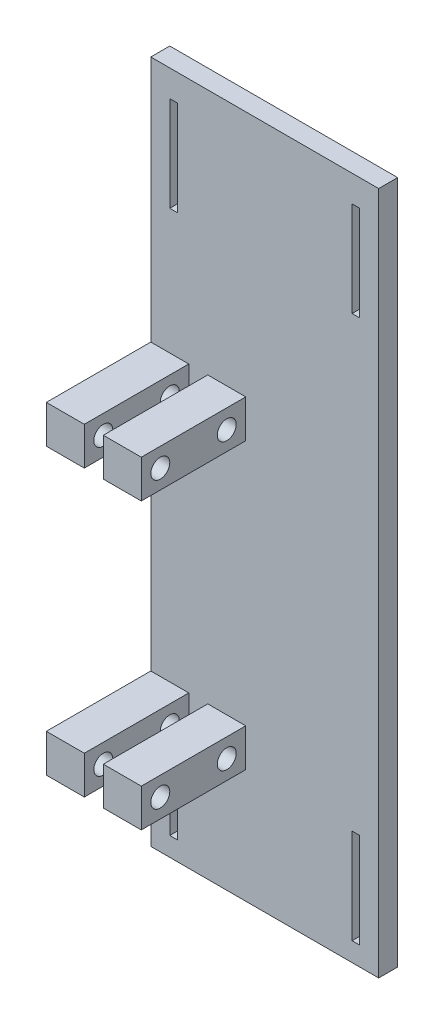
SolidWorks part; units mm, degrees
ref_plane "Alzado" through (0, 0, 0) normal (0, 0, 1) x (1, 0, 0)
ref_plane "Planta" through (0, 0, 0) normal (0, 1, 0) x (1, 0, 0)
ref_plane "Vista lateral" through (0, 0, 0) normal (1, 0, 0) x (0, 0, -1)
sketch "Croquis1" plane through (0, 0, 0) normal (0, 0, 1) x (1, 0, 0)
  line L1 (0, 0) -> (60, 0)
  line L2 (0, 0) -> (0, 170)
  line L3 (0, 170) -> (60, 170)
  line L4 (60, 0) -> (60, 170)
  dimension "D1" = 170
  dimension "D2" = 60
extrude "Saliente-Extruir1" add sketch "Croquis1" along normal blind 5
sketch "Croquis2" plane through (0, 0, 5) normal (0, 0, 1) x (1, 0, 0)
  line L0 (0, 170) -> (0, 0) construction
  line L1 (0, 105) -> (10, 105)
  line L2 (0, 105) -> (0, 95)
  line L3 (0, 95) -> (10, 95)
  line L4 (10, 105) -> (10, 95)
  line L5 (60, 170) -> (0, 170) construction
  line L6 (0, 30) -> (10, 30)
  line L7 (0, 30) -> (0, 20)
  line L8 (0, 20) -> (10, 20)
  line L9 (10, 30) -> (10, 20)
  line L11 (10, 105) -> (15, 105)
  line L12 (10, 105) -> (10, 95)
  line L13 (10, 95) -> (15, 95)
  line L14 (15, 105) -> (15, 95)
  line L15 (10, 30) -> (15, 30)
  line L16 (10, 30) -> (10, 20)
  line L17 (10, 20) -> (15, 20)
  line L18 (15, 30) -> (15, 20)
  line L19 (15, 105) -> (25, 105)
  line L20 (15, 105) -> (15, 95)
  line L21 (15, 95) -> (25, 95)
  line L22 (25, 105) -> (25, 95)
  line L23 (15, 30) -> (25, 30)
  line L24 (15, 30) -> (15, 20)
  line L25 (15, 20) -> (25, 20)
  line L26 (25, 30) -> (25, 20)
  line M11 (0, 170) -> (0, 0)
  dimension "D1" = 65
  dimension "D2" = 10
  dimension "D3" = 10
  dimension "D4" = 65
  dimension "D5" = 10
  dimension "D6" = 10
  dimension "D7" = 5
  dimension "D8" = 5
  dimension "D9" = 10
  dimension "D10" = 10
extrude "Saliente-Extruir2" add sketch "Croquis2" along normal blind 27.5 contours L22 L19 L14 L21 | L4 L1 L3 M11 | L26 L23 L18 L25 | L9 L6 L8 M11
sketch "Croquis3" plane through (25, 0, 0) normal (1, 0, 0) x (0, 0, -1)
  line L0 (-32.5, 95) -> (-5, 95) construction
  line L1 (-5, 105) -> (-5, 95) construction
  line L2 (-32.5, 105) -> (-32.5, 95) construction
  line L3 (-32.5, 30) -> (-5, 30) construction
  line L4 (-32.5, 30) -> (-32.5, 20) construction
  line L5 (-5, 30) -> (-5, 20) construction
  circle A0 centre (-27.5, 100) radius 2.5
  circle A1 centre (-10, 100) radius 2.5
  circle A2 centre (-27.5, 25) radius 2.5
  circle A3 centre (-10, 25) radius 2.5
  dimension "D5" = 5
  dimension "D6" = 5
  dimension "D9" = 5
  dimension "D10" = 5
  dimension "D1" = 5
  dimension "D2" = 5
  dimension "D3" = 5
  dimension "D4" = 5
  dimension "D7" = 5
  dimension "D8" = 5
  dimension "D11" = 5
  dimension "D12" = 5
  dimension "D13" = 17.5
extrude "Cortar-Extruir1" cut sketch "Croquis3" against normal blind 27.5
sketch "Croquis4" plane through (0, 0, 5) normal (0, 0, 1) x (1, 0, 0)
  line L0 (0, 0) -> (60, 0) construction
  line L1 (5, 163) -> (7, 163)
  line L2 (5, 163) -> (5, 138)
  line L3 (5, 138) -> (7, 138)
  line L4 (7, 163) -> (7, 138)
  line L5 (53, 163) -> (55, 163)
  line L6 (53, 163) -> (53, 138)
  line L7 (53, 138) -> (55, 138)
  line L8 (55, 163) -> (55, 138)
  line L9 (43.1199, 23.1761) -> (45.1199, 23.1761)
  line L10 (43.1199, 23.1761) -> (43.1199, 5)
  line L11 (43.1199, 5) -> (45.1199, 5)
  line L12 (45.1199, 23.1761) -> (45.1199, 5)
  line L13 (5, 5) -> (7, 5)
  line L14 (5, 5) -> (5, 30)
  line L15 (5, 30) -> (7, 30)
  line L16 (7, 5) -> (7, 30)
  line L17 (60, 170) -> (0, 170) construction
  line L18 (0, 170) -> (0, 105) construction
  line L19 (60, 0) -> (60, 170) construction
  dimension "D1" = 2
  dimension "D2" = 2
  dimension "D3" = 2
  dimension "D4" = 2
  dimension "D5" = 5
  dimension "D6" = 5
  dimension "D7" = 25
  dimension "D8" = 25
  dimension "D9" = 25
  dimension "D10" = 7
  dimension "D11" = 7
  dimension "D12" = 5
  dimension "D13" = 5
extrude "Cortar-Extruir2" cut sketch "Croquis4" against normal blind 27.5 contours L6 L5 L8 L7 | L2 L1 L4 L3
ref_plane "Plano1" through (0, 20, 5) normal (0, -1, 0) x (-1, 0, 0)
sketch "Croquis6" plane through (0, 0, 0) normal (0, -1, 0) x (1, 0, 0)
  line L1 (0, 5) -> (60, 5)
  line L2 (0, 5) -> (0, 0)
  line L3 (0, 0) -> (60, 0)
  line L4 (60, 5) -> (60, 0)
extrude "Saliente-Extruir3" add sketch "Croquis6" along normal blind 10
sketch "Croquis7" plane through (0, 0, 5) normal (0, 0, 1) x (1, 0, 0)
  line L0 (0, 20) -> (0, -10) construction
  line L1 (5, 20) -> (7, 20)
  line L2 (5, 20) -> (5, -5)
  line L3 (5, -5) -> (7, -5)
  line L4 (7, 20) -> (7, -5)
  line L5 (53, 20) -> (55, 20)
  line L6 (53, 20) -> (53, -5)
  line L7 (53, -5) -> (55, -5)
  line L8 (55, 20) -> (55, -5)
  line L9 (60, -10) -> (60, 170) construction
  line L10 (60, -10) -> (0, -10) construction
  dimension "D1" = 25
  dimension "D2" = 25
  dimension "D3" = 2
  dimension "D4" = 2
  dimension "D5" = 5
  dimension "D6" = 5
  dimension "D7" = 5
  dimension "D8" = 5
extrude "Cortar-Extruir3" cut sketch "Croquis7" against normal blind 10
